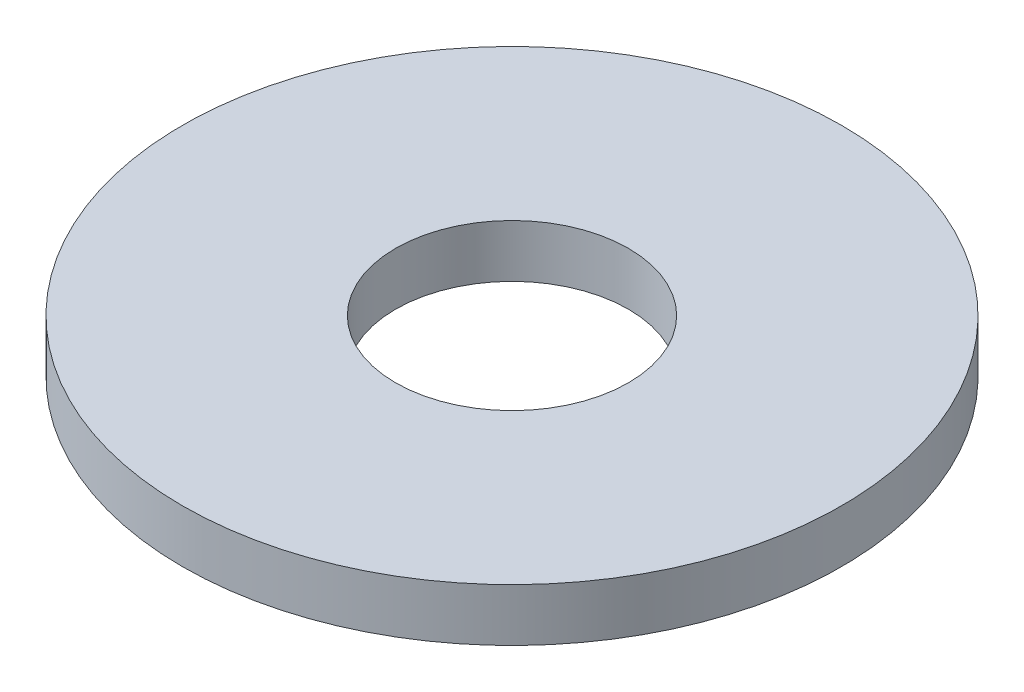
SolidWorks part; units mm, degrees
ref_plane "Plan de face" through (0, 0, 0) normal (0, 0, 1) x (1, 0, 0)
ref_plane "Plan de dessus" through (0, 0, 0) normal (0, 1, 0) x (1, 0, 0)
ref_plane "Plan de droite" through (0, 0, 0) normal (1, 0, 0) x (0, 0, -1)
sketch "Esquisse1" plane through (0, 0, 0) normal (0, 1, 0) x (1, 0, 0)
  circle A0 centre (0, 0) radius 2.65
  circle A1 centre (0, 0) radius 7.5
  dimension "D1" = 5.3
  dimension "D2" = 15
extrude "Boss.-Extru.1" add sketch "Esquisse1" along normal blind 1.2
